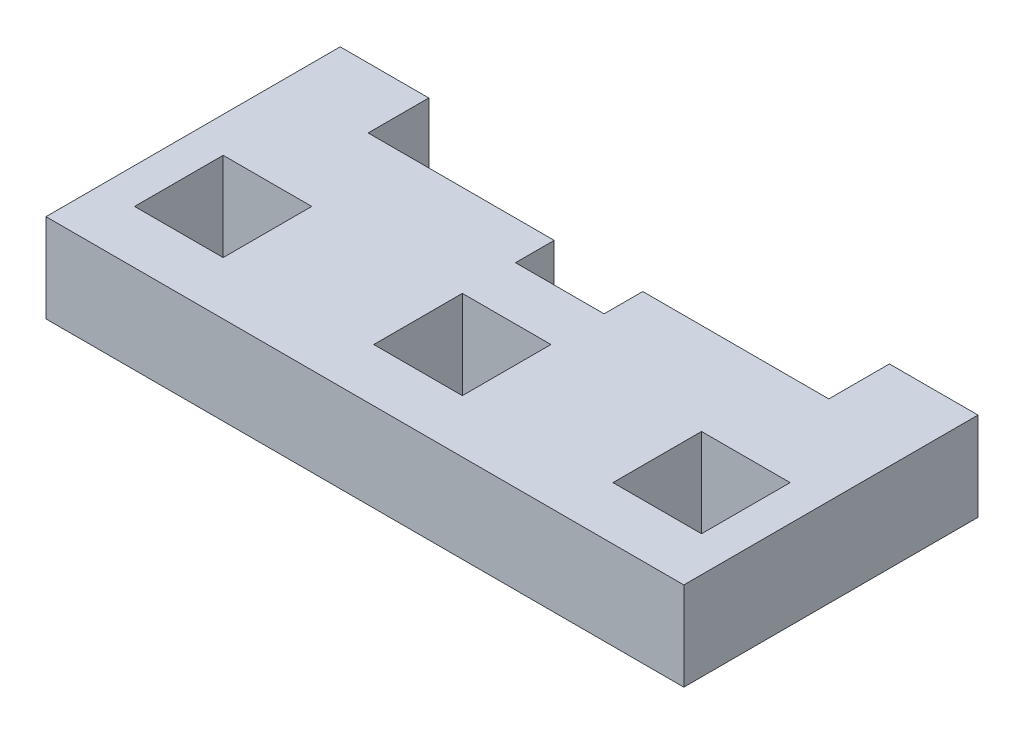
SolidWorks part; units mm, degrees
ref_plane "Front Plane" through (0, 0, 0) normal (0, 0, 1) x (1, 0, 0)
ref_plane "Top Plane" through (0, 0, 0) normal (0, 1, 0) x (1, 0, 0)
ref_plane "Right Plane" through (0, 0, 0) normal (1, 0, 0) x (0, 0, -1)
sketch "Sketch1" plane through (0, 0, 0) normal (0, 1, 0) x (1, 0, 0)
  line L0 (-22.86, 0) -> (22.86, 0) construction
  line L1 (-22.86, -6.985) -> (22.86, -6.985)
  line L2 (-22.86, -6.985) -> (-22.86, 9.7575)
  line L3 (-16.51, 9.7575) -> (-3.175, 9.7575)
  line L4 (22.86, -6.985) -> (22.86, 9.7575)
  line L5 (0, 6.985) -> (0, -6.985) construction
  line L6 (-3.175, 9.7575) -> (-3.175, 6.985)
  line L7 (-3.175, 6.985) -> (3.175, 6.985)
  line L8 (3.175, 6.985) -> (3.175, 9.7575)
  line L9 (3.175, 9.7575) -> (16.51, 9.7575)
  line L10 (-20.32, 3.175) -> (-13.97, -3.175) construction
  line L11 (-3.175, 3.175) -> (3.175, 3.175)
  line L12 (-3.175, 3.175) -> (-3.175, -3.175)
  line L13 (-3.175, -3.175) -> (3.175, -3.175)
  line L15 (22.86, 9.7575) -> (22.86, 14.1025)
  line L16 (3.175, 3.175) -> (3.175, -3.175)
  line L17 (-3.175, 3.175) -> (3.175, -3.175) construction
  line L18 (-3.175, -3.175) -> (3.175, 3.175) construction
  line L19 (-13.97, 3.175) -> (-20.32, -3.175) construction
  line L20 (13.97, 3.175) -> (20.32, -3.175) construction
  line L21 (13.97, -3.175) -> (20.32, 3.175) construction
  line L22 (20.32, -3.175) -> (13.97, -3.175)
  line L23 (20.32, -3.175) -> (20.32, 3.175)
  line L24 (20.32, 3.175) -> (13.97, 3.175)
  line L25 (13.97, -3.175) -> (13.97, 3.175)
  line L26 (22.86, 14.1025) -> (16.51, 14.1025)
  line L27 (16.51, 14.1025) -> (16.51, 9.7575)
  line L28 (-16.51, 14.1025) -> (-16.51, 9.7575)
  line L29 (-22.86, 14.1025) -> (-16.51, 14.1025)
  line L30 (-13.97, -3.175) -> (-13.97, 3.175)
  line L31 (-20.32, 3.175) -> (-13.97, 3.175)
  line L32 (-20.32, -3.175) -> (-20.32, 3.175)
  line L33 (-20.32, -3.175) -> (-13.97, -3.175)
  line L34 (-22.86, 9.7575) -> (-22.86, 14.1025)
  point P8 (0, 0)
  point P12 (0, 6.985)
  point P16 (0, 0)
  point P22 (-17.145, 0)
  point P23 (17.145, 0)
  dimension "D1" = 45.72
  dimension "D2" = 3.81
  dimension "D3" = 6.35
  dimension "D4" = 3.81
  dimension "D5" = 13.97
  dimension "D6" = 6.35
  dimension "D7" = 2.54
  dimension "D8" = 10.795
  dimension "D9" = 2.7725
  dimension "D10" = 4.345
  dimension "D11" = 6.35
extrude "Boss-Extrude1" add sketch "Sketch1" along normal blind 6.35
equation "\"Ball Diameter\"= 1.75in"
equation "\"Sheet Thickness\"= 0.25in"
equation "\"Screw Diameter\"= .17in"
equation "\"Robot Diameter\"= 14in"
equation "\"Castor Screw Diameter\"= 0.22in"
equation "\"Wheel Diameter\" = 4in"
equation "\"Nut Diameter\" = 8.4mm"
equation "\"Nut Height\" = 2.9mm"
equation "\"Screw Height\" = 0.55in"
equation "\"Pulley Diameter\" = 1in"
equation "\"Reactor Height\" = 14in"
equation "\"Elevator Height\" = 11.5in"
equation "\"Elevator Width\" = \"Ball Diameter\" + 0.25in"
equation "\"Elevator Bearing Diameter\" = sqr(2*(\"Sheet Thickness\"^2)) + 0.2in"
equation "\"Elevator Axle Endcap Diameter\" = \"Pulley Diameter\" + 0.25in"
equation "\"Elevator Axle Length\" = \"Elevator Width\" + 8*\"Sheet Thickness\""
equation "\"Elevator Clearance from Axis\" = (\"Pulley Diameter\"/2) + \"Ball Diameter\" + 0.5in"
equation "\"D1@Sketch1\"=\"Elevator Width\"-0.2in"
equation "\"D3@Sketch1\" = \"Sheet Thickness\""
equation "\"D6@Sketch1\"=\"Sheet Thickness\""
equation "\"D9@Sketch1\"=(0.3in - ((\"Elevator Axle Endcap Diameter\"-\"Pulley Diameter\")/2 - 1.1mm))/2"
equation "\"D10@Sketch1\"=(\"Elevator Axle Endcap Diameter\"-\"Pulley Diameter\")/2 - 1.1mm + 2.27mm"
equation "\"D1@Boss-Extrude1\"=\"Sheet Thickness\""
equation "\"Ball Radius\" = \"Ball Diameter\"/2"
equation "\"Claw Horizontal Seperation\" = (\"Elevator Width\"/2) - (1.5 * \"Sheet Thickness\") - 0.15in"
